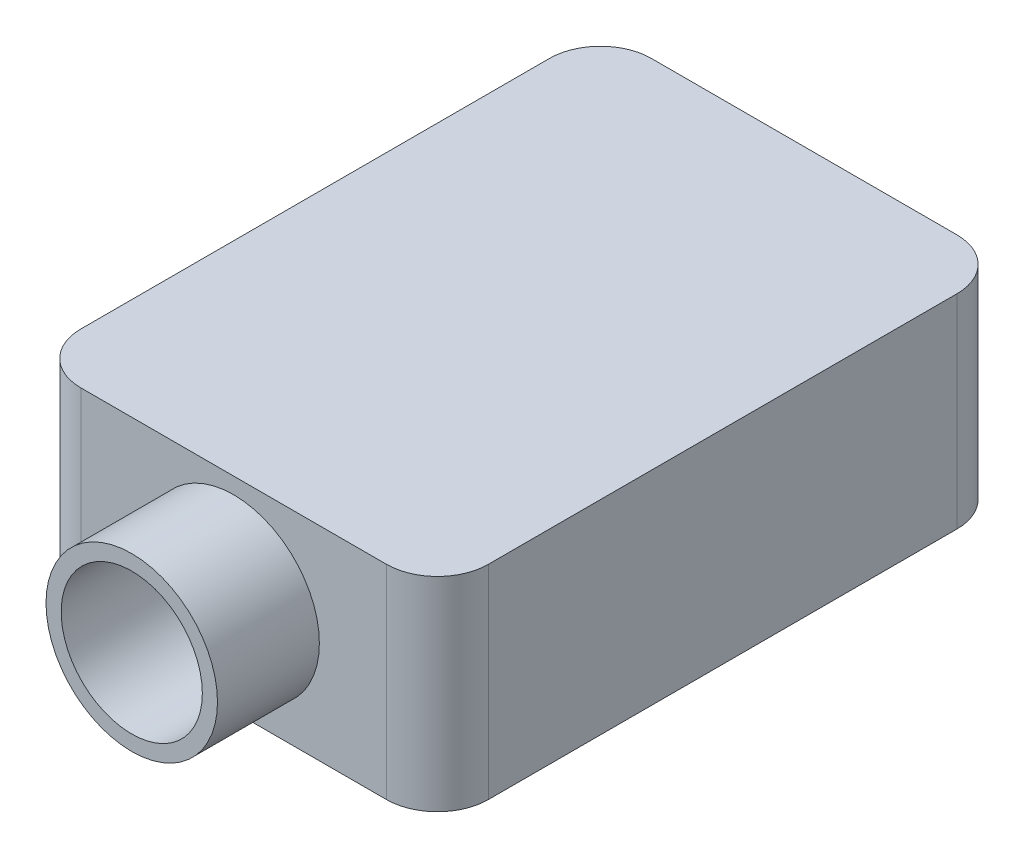
SolidWorks part; units mm, degrees
ref_plane "前视基准面" through (0, 0, 0) normal (0, 0, 1) x (1, 0, 0)
ref_plane "上视基准面" through (0, 0, 0) normal (0, 1, 0) x (1, 0, 0)
ref_plane "右视基准面" through (0, 0, 0) normal (1, 0, 0) x (0, 0, -1)
sketch "草图2" plane through (0, 0, 0) normal (0, 1, 0) x (1, 0, 0)
  line L1 (-20, -28) -> (20, -28)
  line L2 (-20, -28) -> (-20, 28)
  line L3 (-20, 28) -> (20, 28)
  line L4 (20, -28) -> (20, 28)
  line L5 (-20, -28) -> (20, 28) construction
  line L6 (-20, 28) -> (20, -28) construction
  point P0 (0, 0)
extrude "凸台-拉伸1" add sketch "草图2" along normal blind 20
sketch "草图3" plane through (0, 0, 28) normal (0, 0, 1) x (1, 0, 0)
  circle A0 centre (0, 10) radius 8.4156
  circle A1 centre (0, 10) radius 6.9284
extrude "凸台-拉伸2" add sketch "草图3" along normal blind 10
fillet "圆角1" radius 5 4 edges at (-20, 10, -28) (-20, 10, 28) (20, 10, -28) (20, 10, 28)
